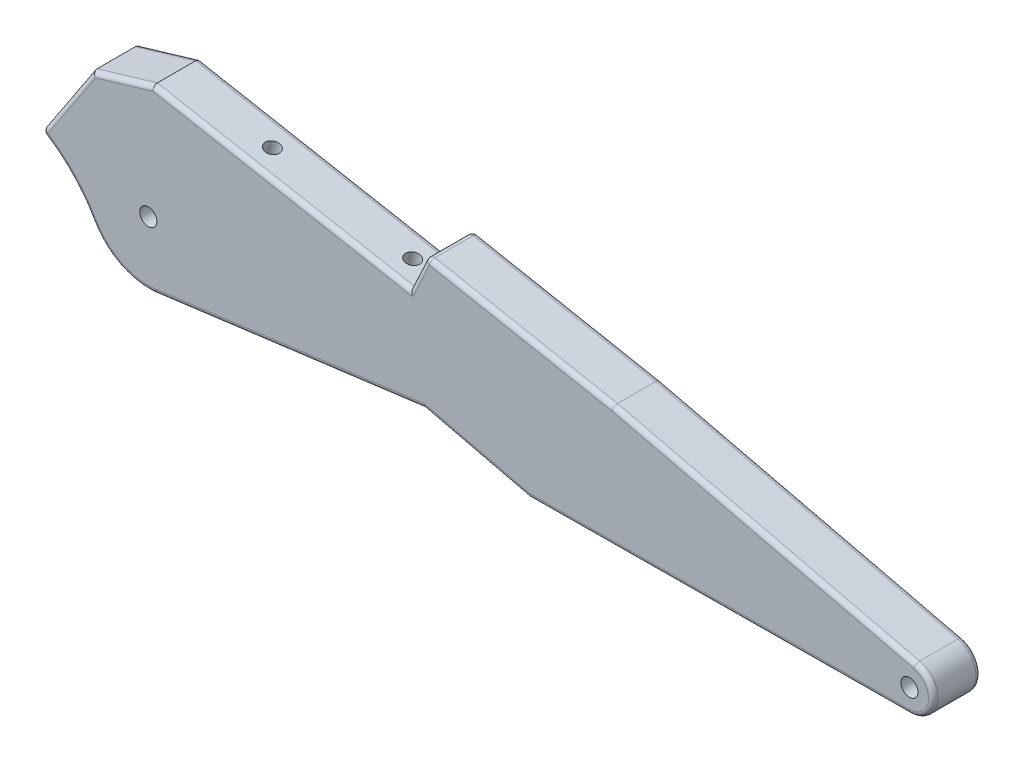
SolidWorks part; units mm, degrees
ref_plane "Front Plane" through (0, 0, 0) normal (0, 0, 1) x (1, 0, 0)
ref_plane "Top Plane" through (0, 0, 0) normal (0, 1, 0) x (1, 0, 0)
ref_plane "Right Plane" through (0, 0, 0) normal (1, 0, 0) x (0, 0, -1)
sketch "Sketch1" plane through (0, 0, 0) normal (0, 0, 1) x (1, 0, 0)
  line L1 (0.0486, -6.3498) -> (-101.5514, -7.1275)
  line L2 (-101.5514, -7.1275) -> (-129.54, -0.456)
  line L6 (-128.905, 34.925) -> (-133.35, 25.4)
  line L7 (-200.977, -9.7973) -> (-129.54, -0.456)
  line L8 (-133.35, 25.4) -> (-202.0358, 38.1)
  line L9 (-202.0358, 38.1) -> (-218.1154, 33.3375)
  line L10 (-128.905, 34.925) -> (-79.1726, 25.4)
  line L11 (-79.1726, 25.4) -> (-128.905, 34.925) construction
  line L12 (-79.1726, 25.4) -> (1.4724, 6.1769)
  line L13 (-129.5991, 33.4375) -> (-133.35, 25.4) construction
  line L17 (-133.35, 25.4) -> (-202.0358, 38.1) construction
  line L18 (-17.145, -27.2472) -> (-129.54, -0.456) construction
  line L19 (-200.977, -9.7973) -> (-129.54, -0.456) construction
  line L20 (-107.0451, 30.7383) -> (-127.6185, 34.6786) construction
  line L21 (-180.2576, 44.5503) -> (-218.1154, 33.3375) construction
  line L22 (-231.775, 12.7) -> (-218.1154, 33.3375)
  line L23 (-218.1154, 33.3375) -> (-273.7845, -50.7694) construction
  line L24 (-17.145, -27.2472) -> (-129.54, -0.456) construction
  line L29 (-79.1726, 25.4) -> (1.4724, 6.1769) construction
  line L31 (-129.54, -0.456) -> (-200.977, -9.7973) construction
  circle A0 centre (0, 0) radius 2.286
  arc A1 (0.0486, -6.3498) -> (1.4724, 6.1769) centre (0, 0) ccw
  circle A2 centre (-203.2, 7.203) radius 2.286
  arc A6 (-218.1154, -1.2518) -> (-200.977, -9.7973) centre (-203.2, 7.203) ccw
  circle A7 centre (-203.2, 7.203) radius 2.286 construction
  arc A8 (4.6019, -4.3755) -> (1.4724, 6.1769) centre (0, 0) ccw construction
  arc A10 (-200.977, -9.7973) -> (-218.1154, -1.2518) centre (-203.2, 7.203) ccw construction
  arc A11 (-218.1154, -1.2518) -> (-231.775, 12.7) centre (-251.2606, -20.0402) ccw
  arc A12 (-231.775, 12.7) -> (-218.1154, -1.2518) centre (-251.2606, -20.0402) ccw construction
  point P17 (105.4504, -19.602)
  point P18 (-71.2573, 0.0759)
  point P26 (-101.9879, -7.0235)
  dimension "D1" = 4.572
  dimension "D2" = 101.6
extrude "Boss-Extrude1" add sketch "Sketch1" along normal blind 12.7
fillet "Fillet1" radius 1.27 26 edges at (-165.2585, -5.1266, 12.7) (-210.8505, -8.1405, 12.7) (-38.8501, 15.7885, 12.7) (-224.0363, 6.614, 0) (-210.8505, -8.1405, 0) (-50.7514, -6.7387, 0) (-224.0363, 6.614, 12.7) (-224.9452, 23.0188, 12.7) (-210.0756, 35.7188, 12.7) (-167.6929, 31.75, 12.7) (-131.1275, 30.1625, 0) (-131.1275, 30.1625, 12.7) (-104.0388, 30.1625, 12.7) (-115.5457, -3.7917, 12.7) (-50.7514, -6.7387, 12.7) (-210.0756, 35.7188, 0) (-224.9452, 23.0188, 0) (-167.6929, 31.75, 0) (-128.905, 34.925, 6.35) (-165.2585, -5.1266, 0) (-115.5457, -3.7917, 0) (-38.8501, 15.7885, 0) (-104.0388, 30.1625, 0) (6.3094, -0.7171, 12.7) (6.3094, -0.7171, 0) (-231.775, 12.7, 6.35)
sketch "Sketch2" plane through (0, 0, 0) normal (0, 0, -1) x (-1, 0, 0)
  circle A0 centre (0, 0) radius 4.445
  dimension "D1" = 8.89
extrude "Cut-Extrude1" cut sketch "Sketch2" against normal blind 3.9688
sketch "Sketch3" plane through (0.1329, 0.719, 0) normal (0.1818, 0.9833, 0) x (0.9833, -0.1818, 0)
  circle A0 centre (-179.5561, -6.35) radius 1.905
  circle A1 centre (-141.4561, -6.35) radius 1.905
  dimension "D1" = 3.81
extrude "Cut-Extrude2" cut sketch "Sketch3" against normal blind 12.7
sketch "Sketch4" plane through (-167.0137, 110.5438, 0) normal (-0.8339, 0.5519, 0) x (0, 0, 1)
  line L0 (0, -116.025) -> (0, -93.0484) construction
  line L1 (1.27, -117.295) -> (11.43, -117.295) construction
  circle A0 centre (6.35, -110.945) radius 1.905
  point P4 (0, 0)
  dimension "D1" = 3.81
  dimension "D2" = 6.35
  dimension "D3" = 6.35
extrude "Cut-Extrude3" cut sketch "Sketch4" against normal blind 12.7
